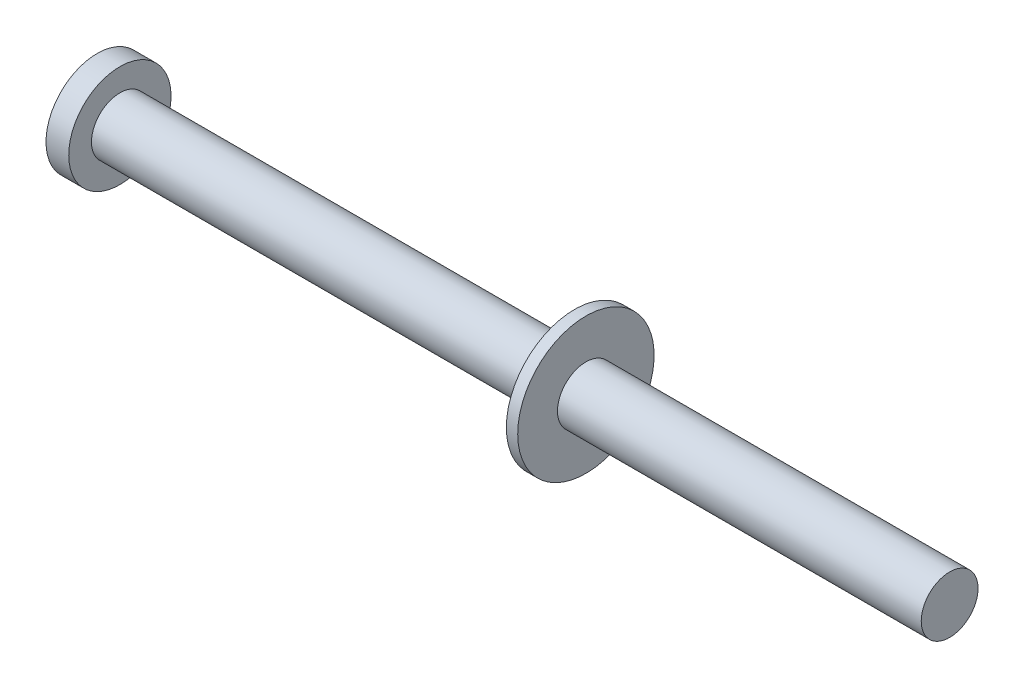
SolidWorks part; units mm, degrees
ref_plane "Front Plane" through (0, 0, 0) normal (0, 0, 1) x (1, 0, 0)
ref_plane "Top Plane" through (0, 0, 0) normal (0, 1, 0) x (1, 0, 0)
ref_plane "Right Plane" through (0, 0, 0) normal (1, 0, 0) x (0, 0, -1)
sketch "Sketch1" plane through (0, 0, 0) normal (0, 1, 0) x (1, 0, 0)
  line L0 (-75, 0) -> (75, 0)
  line L1 (-75, 0) -> (-75, 9)
  line L2 (-75, 9) -> (-71, 9)
  line L3 (-71, 9) -> (-71, 5)
  line L4 (-71, 5) -> (9, 5)
  line L5 (9, 5) -> (9, 12)
  line L6 (9, 12) -> (11, 12)
  line L7 (11, 12) -> (11, 5)
  line L8 (11, 5) -> (75, 5)
  line L9 (75, 5) -> (75, 0)
  point P3 (0, 0)
  dimension "D1" = 150
  dimension "D2" = 9
  dimension "D3" = 5
  dimension "D4" = 80
  dimension "D5" = 4
  dimension "D6" = 64
  dimension "D7" = 12
revolve "Revolve1" add sketch "Sketch1" angle 360 about L0
